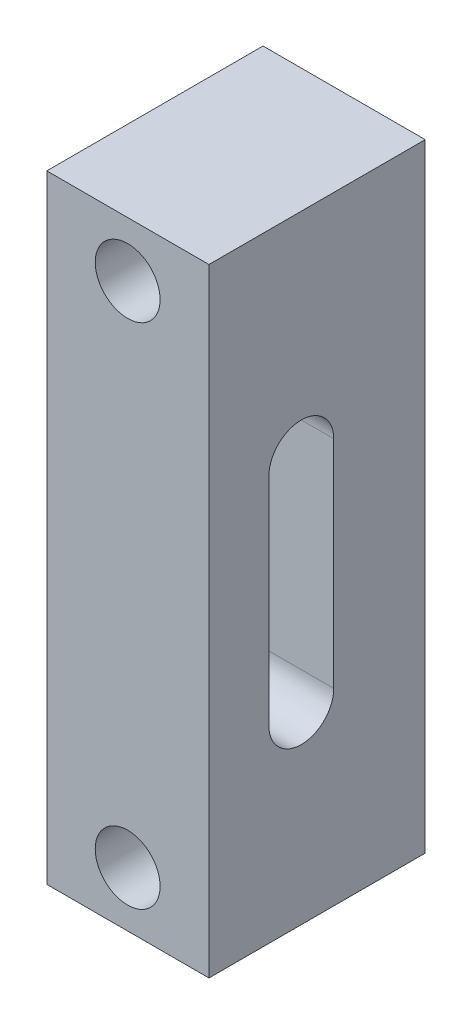
SolidWorks part; units mm, degrees
ref_plane "Front Plane" through (0, 0, 0) normal (0, 0, 1) x (1, 0, 0)
ref_plane "Top Plane" through (0, 0, 0) normal (0, 1, 0) x (1, 0, 0)
ref_plane "Right Plane" through (0, 0, 0) normal (1, 0, 0) x (0, 0, -1)
sketch "Sketch1" plane through (0, 0, 0) normal (0, 0, 1) x (1, 0, 0)
  line L1 (27.4661, -151.9069) -> (42.4661, -151.9069)
  line L2 (27.4661, -151.9069) -> (27.4661, -209.0569)
  line L3 (27.4661, -209.0569) -> (42.4661, -209.0569)
  line L4 (42.4661, -151.9069) -> (42.4661, -209.0569)
  dimension "D1" = 15
  dimension "D2" = 57.15
extrude "Boss-Extrude1" add sketch "Sketch1" along normal blind 20
sketch "Sketch2" plane through (0, 0, 0) normal (0, 0, -1) x (-1, 0, 0)
  point P0 (-34.9461, -156.9869)
  point P1 (-34.9461, -203.9769)
hole_wizard "Ø6.0 (6) Diameter Hole1" positions "Sketch4" profile "Sketch3" hole size "Ø6.0" standard "ANSI Metric"
sketch "Sketch4" plane through (0, 0, 0) normal (0, 0, -1) x (-1, 0, 0)
  point P0 (-34.9461, -156.9869)
  point P3 (-34.9461, -203.9769)
sketch "Sketch3" plane through (34.9461, -156.9869, 0) normal (1, 0, 0) x (0, 1, 0)
  line L0 (0, 0) -> (0, 25.8026)
  line L1 (0, 25.8026) -> (3, 24)
  line L2 (3, 24) -> (3, 0)
  line L5 (3, 0) -> (0, 0)
  line L10 (0, 25.8026) -> (-3, 24) construction
  line L11 (0, -6.35) -> (0, 107.95) construction
  dimension "Hole Dia." = 6
  dimension "Hole Depth" = 24
  dimension "Drill Angle" = 118
sketch "Sketch5" plane through (42.4661, 0, 0) normal (1, 0, 0) x (0, 0, -1)
  line L0 (-11.46, -181.6298) -> (-11.46, -191.6298) construction
  line L1 (-11.46, -181.6298) -> (-11.46, -171.6298) construction
  line L2 (-14.46, -171.6298) -> (-14.46, -191.6298)
  line L3 (-8.46, -191.6298) -> (-8.46, -171.6298)
  arc A0 (-8.46, -171.6298) -> (-14.46, -171.6298) centre (-11.46, -171.6298) ccw
  arc A1 (-14.46, -191.6298) -> (-8.46, -191.6298) centre (-11.46, -191.6298) ccw
  point P0 (-11.46, -181.6298)
  dimension "D1" = 10
  dimension "D2" = 10
extrude "Cut-Extrude1" cut sketch "Sketch5" against normal through all
